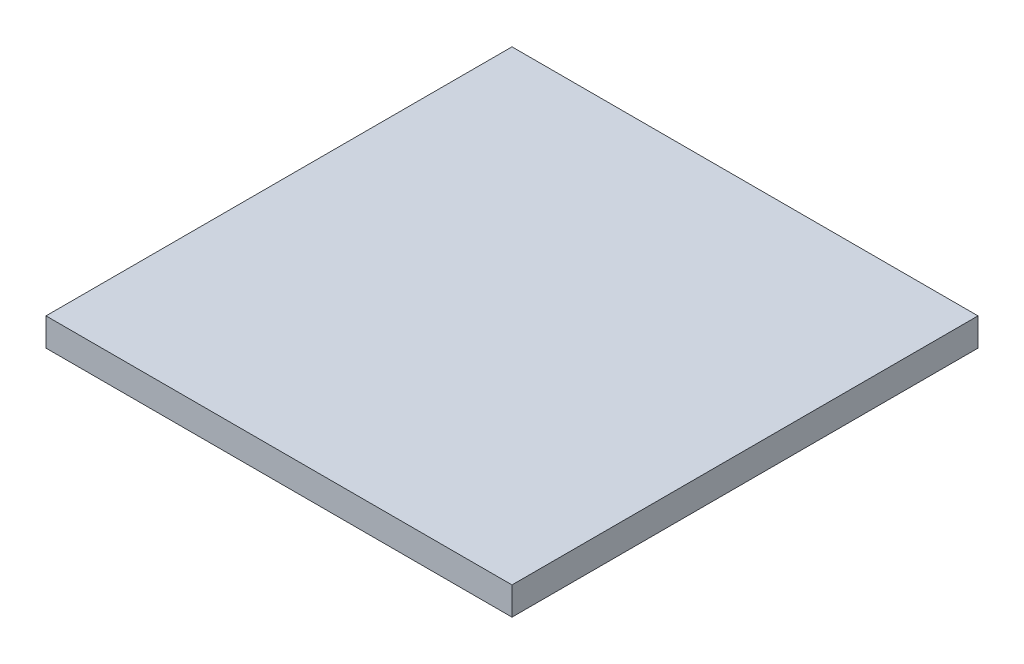
SolidWorks part; units mm, degrees
ref_plane "Front Plane" through (0, 0, 0) normal (0, 0, 1) x (1, 0, 0)
ref_plane "Top Plane" through (0, 0, 0) normal (0, 1, 0) x (1, 0, 0)
ref_plane "Right Plane" through (0, 0, 0) normal (1, 0, 0) x (0, 0, -1)
sketch "Sketch1" plane through (0, 0, 0) normal (0, 1, 0) x (1, 0, 0)
  line L1 (-50, -50) -> (50, -50)
  line L2 (-50, -50) -> (-50, 50)
  line L3 (-50, 50) -> (50, 50)
  line L4 (50, -50) -> (50, 50)
  line L5 (-50, -50) -> (50, 50) construction
  line L6 (-50, 50) -> (50, -50) construction
  point P0 (0, 0)
  dimension "D1" = 100
extrude "Boss-Extrude1" add sketch "Sketch1" along normal blind 6
